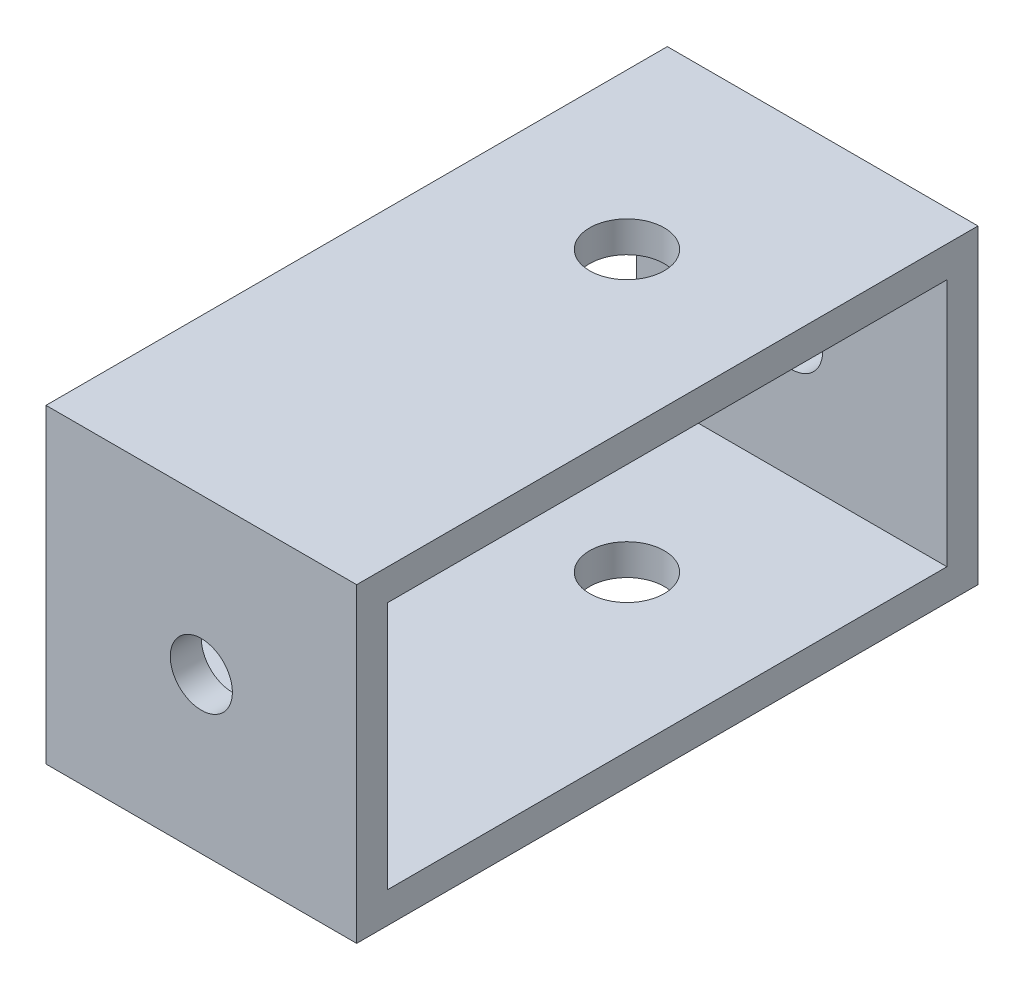
SolidWorks part; units mm, degrees
ref_plane "Front Plane" through (0, 0, 0) normal (0, 0, 1) x (1, 0, 0)
ref_plane "Top Plane" through (0, 0, 0) normal (0, 1, 0) x (1, 0, 0)
ref_plane "Right Plane" through (0, 0, 0) normal (1, 0, 0) x (0, 0, -1)
sketch "Sketch1" plane through (0, 0, 0) normal (1, 0, 0) x (0, 0, -1)
  line L0 (2.54, 22.86) -> (2.54, 2.54)
  line L1 (0, 25.4) -> (50.8, 25.4)
  line L2 (0, 25.4) -> (0, 0)
  line L3 (0, 0) -> (50.8, 0)
  line L4 (50.8, 25.4) -> (50.8, 0)
  line L5 (2.54, 2.54) -> (48.26, 2.54)
  line L6 (48.26, 22.86) -> (48.26, 2.54)
  line L7 (2.54, 22.86) -> (48.26, 22.86)
  dimension "D1" = 50.8
  dimension "D2" = 25.4
  dimension "D3" = 2.54
extrude "Boss-Extrude1" add sketch "Sketch1" along normal blind 25.4 contours L2 L3 L4 L1 | L0 L5 L6 L7
sketch "Sketch3" plane through (0, 25.4, 0) normal (0, 1, 0) x (1, 0, 0)
  line L1 (25.4, 0) -> (0, 0) construction
  line L2 (12.7, 0) -> (12.7, 50.8) construction
  line L3 (25.4, 50.8) -> (0, 50.8) construction
  circle A0 centre (12.7, 34.798) radius 3.048
  dimension "D1" = 16.002
  dimension "D2" = 6.096
extrude "Cut-Extrude1" cut sketch "Sketch3" against normal through all contours A0
sketch "Sketch4" plane through (0, 0, 0) normal (0, 0, 1) x (1, 0, 0)
  line L0 (12.7, 25.4) -> (12.7, 0) construction
  line L1 (25.4, 25.4) -> (0, 25.4) construction
  line L2 (25.4, 0) -> (0, 0) construction
  line L3 (0, 12.7) -> (25.4, 12.7) construction
  line L4 (0, 25.4) -> (0, 0) construction
  line L5 (25.4, 25.4) -> (25.4, 0) construction
  circle A0 centre (12.7, 12.7) radius 2.54
  point P14 (16.3455, 10.7489)
  point P15 (15.9226, 11.093)
  point P16 (12.7, 12.7)
  dimension "D1" = 5.08
extrude "Cut-Extrude2" cut sketch "Sketch4" against normal through all
